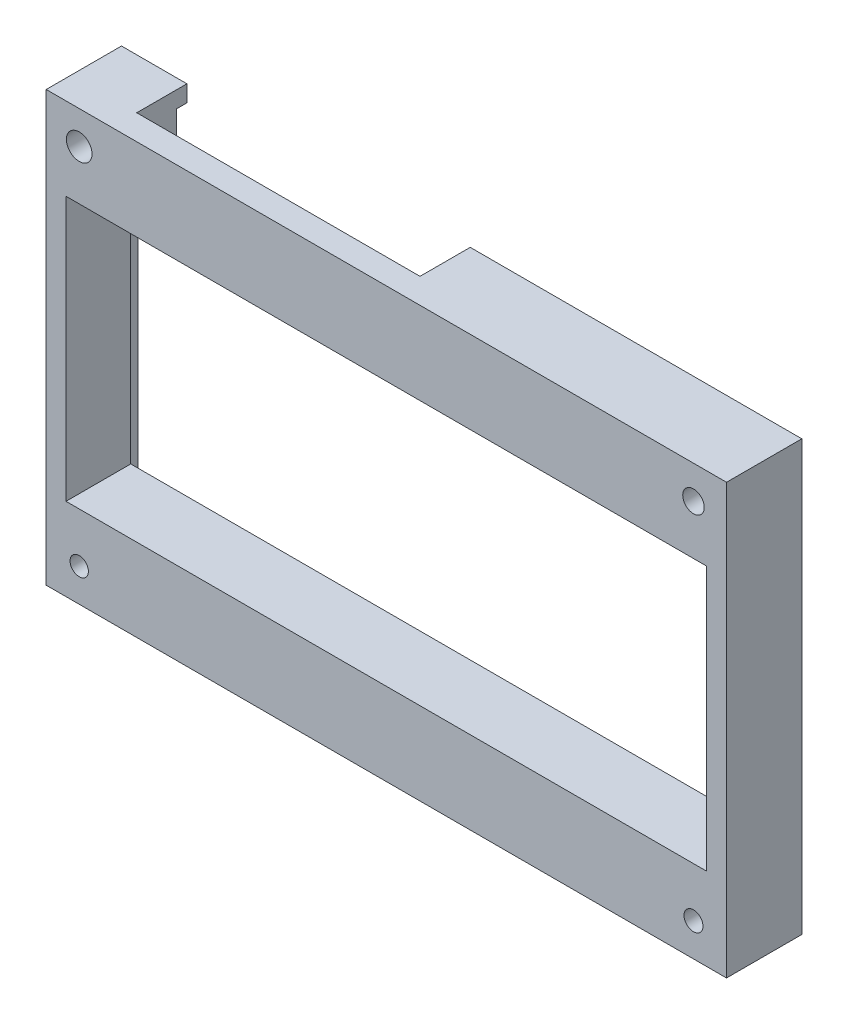
SolidWorks part; units mm, degrees
material "PE High Density"
ref_plane "Front Plane" through (0, 0, 0) normal (0, 0, 1) x (1, 0, 0)
ref_plane "Top Plane" through (0, 0, 0) normal (0, 1, 0) x (1, 0, 0)
ref_plane "Right Plane" through (0, 0, 0) normal (1, 0, 0) x (0, 0, -1)
sketch "Sketch2" plane through (0, 0, 0) normal (0, 0, 1) x (1, 0, 0)
  line L0 (0, 32.5) -> (0, 11.8857) construction
  line L1 (51.5, 32.5) -> (-51.5, 32.5)
  line L2 (51.5, 32.5) -> (51.5, -32.5)
  line L3 (51.5, -32.5) -> (-51.5, -32.5)
  line L4 (-51.5, 32.5) -> (-51.5, -32.5)
  line L5 (51.5, 32.5) -> (-51.5, -32.5) construction
  line L6 (51.5, -32.5) -> (-51.5, 32.5) construction
  line L7 (-51.5, 0) -> (-17.3294, 0) construction
  point P0 (0, 0)
  dimension "D1" = 103
  dimension "D2" = 65
extrude "Boss-Extrude1" add sketch "Sketch2" along normal blind 9.8
sketch "Sketch4" plane through (0, 0, 9.8) normal (0, 0, 1) x (1, 0, 0)
  line L1 (48.5, -20) -> (-48.5, -20)
  line L2 (48.5, -20) -> (48.5, 20)
  line L3 (48.5, 20) -> (-48.5, 20)
  line L4 (-48.5, -20) -> (-48.5, 20)
  line L5 (48.5, -20) -> (-48.5, 20) construction
  line L6 (48.5, 20) -> (-48.5, -20) construction
  point P0 (0, 0)
  dimension "D1" = 97
  dimension "D2" = 40
extrude "Cut-Extrude1" cut sketch "Sketch4" against normal blind 35
sketch "Sketch5" plane through (0, 32.5, 0) normal (0, 1, 0) x (1, 0, 0)
  line L0 (44.1872, -9.8) -> (44.1872, -4.7948)
  line L1 (51.5, -9.8) -> (-51.5, -9.8) construction
  line L2 (44.1872, -4.7948) -> (10.3752, -4.7948)
  line L3 (10.3752, -4.7948) -> (10.3752, -9.8)
  line L4 (10.3752, -9.8) -> (44.1872, -9.8)
sketch "Sketch6" plane through (0, 0, 0) normal (0, 0, -1) x (-1, 0, 0)
  line L0 (-51.5, 32.5) -> (51.5, 32.5) construction
  line L1 (41.5934, 32.5) -> (-1.2969, 32.5)
  line L2 (41.5934, 32.5) -> (41.5934, 22.5568)
  line L3 (41.5934, 22.5568) -> (-1.2969, 22.5568)
  line L4 (-1.2969, 32.5) -> (-1.2969, 22.5568)
extrude "Cut-Extrude3" cut sketch "Sketch6" against normal blind 6
sketch "Sketch9" plane through (0, 0, 0) normal (0, 0, -1) x (-1, 0, 0)
  line L1 (49, -30) -> (-49, -30)
  line L2 (49, -30) -> (49, 30)
  line L3 (49, 30) -> (-49, 30)
  line L4 (-49, -30) -> (-49, 30)
  line L5 (51.5, -32.5) -> (-51.5, -32.5)
  line L6 (51.5, -32.5) -> (51.5, 32.5)
  line L7 (51.5, 32.5) -> (-51.5, 32.5)
  line L8 (-51.5, -32.5) -> (-51.5, 32.5)
extrude "Boss-Extrude2" add sketch "Sketch9" along normal blind 1.6
sketch "Sketch10" plane through (0, 32.5, 0) normal (0, 1, 0) x (1, 0, 0)
  line L0 (1.2969, 0) -> (1.2969, 16.3442)
  line L1 (1.2969, 16.3442) -> (-41.5934, 16.3442)
  line L2 (-41.5934, 16.3442) -> (-41.5934, 0)
  line L3 (-41.5934, 0) -> (1.2969, 0)
extrude "Cut-Extrude4" cut sketch "Sketch10" against normal up to surface (9.9432 mm away) up to face at (-20.1483, 22.5568, 3)
sketch "Sketch14" plane through (0, 0, -1.6) normal (0, 0, -1) x (-1, 0, 0)
  line L5 (46.5, 27.5) -> (-46.5, 27.5)
  line L6 (46.5, 27.5) -> (46.5, -27.5)
  line L7 (46.5, -27.5) -> (-46.5, -27.5)
  line L8 (-46.5, 27.5) -> (-46.5, -27.5)
  line L9 (46.5, 27.5) -> (-46.5, -27.5) construction
  line L10 (46.5, -27.5) -> (-46.5, 27.5) construction
  circle A4 centre (-46.5, 27.5) radius 1.63
  circle A5 centre (46.5, 27.5) radius 1.9386
  circle A6 centre (46.5, -27.5) radius 1.3884
  circle A7 centre (-46.5, -27.5) radius 1.4381
  point P0 (0, 0)
  dimension "D1" = 55
  dimension "D2" = 93
extrude "Cut-Extrude7" cut sketch "Sketch14" along normal blind 28 and the other way blind 33 contours A5 | A4 | A7 | A6
